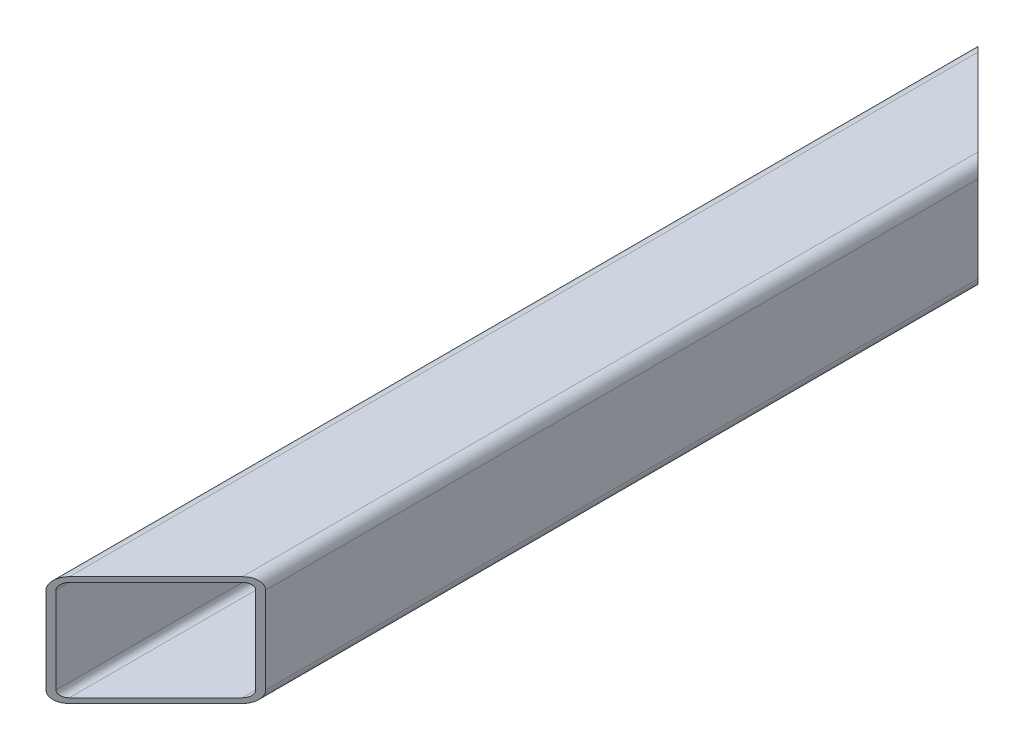
SolidWorks part; units mm, degrees
ref_plane "Спереди" through (0, 0, 0) normal (0, 0, 1) x (1, 0, 0)
ref_plane "Сверху" through (0, 0, 0) normal (0, 1, 0) x (1, 0, 0)
ref_plane "Справа" through (0, 0, 0) normal (1, 0, 0) x (0, 0, -1)
sketch "Эскиз1" plane through (0, 0, 0) normal (0, 0, 1) x (1, 0, 0)
  line L1 (2, 0) -> (28, 0)
  line L2 (0, 2) -> (0, 28)
  line L3 (2, 30) -> (28, 30)
  line L4 (30, 2) -> (30, 28)
  arc A0 (28, 0) -> (30, 2) centre (28, 2) ccw
  arc A1 (30, 28) -> (28, 30) centre (28, 28) ccw
  arc A2 (2, 30) -> (0, 28) centre (2, 28) ccw
  arc A3 (0, 2) -> (2, 0) centre (2, 2) ccw
  point P7 (30, 0)
  point P12 (0, 30)
  point P15 (0, 0)
  dimension "D3" = 2
  dimension "D1" = 30
  dimension "D2" = 30
extrude "Вытянуть-Тонкостенный1" add sketch "Эскиз1" along normal blind 280 thin
sketch "Эскиз2" plane through (0, 31.5, 0) normal (0, 1, 0) x (1, 0, 0)
  line L0 (-1.5, 0) -> (31.5, -33)
  line L1 (31.5, -280) -> (31.5, 0) construction
  line L2 (31.5, -33) -> (31.5, 0)
  line L3 (31.5, 0) -> (-1.5, 0)
  line L4 (-1.5, -280) -> (31.5, -247)
  line L5 (31.5, -247) -> (31.5, -280)
  line L6 (31.5, -280) -> (-1.5, -280)
extrude "Вырез-Вытянуть1" cut sketch "Эскиз2" against normal through all
